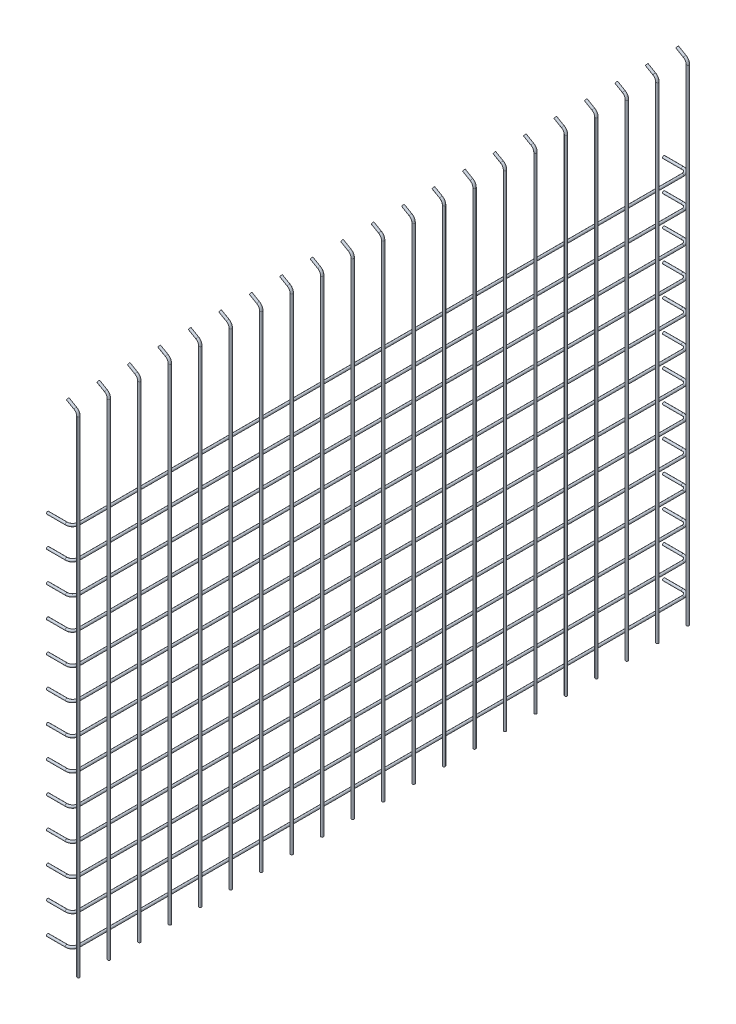
SolidWorks part; units mm, degrees
material "AISI 1020"
ref_plane "Спереди" through (0, 0, 0) normal (0, 0, 1) x (1, 0, 0)
ref_plane "Сверху" through (0, 0, 0) normal (0, 1, 0) x (1, 0, 0)
ref_plane "Справа" through (0, 0, 0) normal (1, 0, 0) x (0, 0, -1)
sketch "Эскиз1" plane through (0, 0, 0) normal (0, 0, 1) x (1, 0, 0)
  line L0 (-2, 0) -> (-2, 796.993)
  line L1 (-7, 805.6532) -> (-19.3205, 812.7665)
  line L2 (-1694.5, 1782.2412) -> (84.6025, 755.0759) construction
  line L3 (-44, 829.3246) -> (0, 803.9212) construction
  arc A0 (-2, 796.993) -> (-7, 805.6532) centre (-12, 796.993) ccw
  point P8 (0, 0)
  point P11 (-2, 802.7665)
  dimension "D4" = 10
  dimension "D1" = 2
  dimension "D2" = 20
  dimension "D3" = 2
ref_plane "Плоскость1" through (0, 0, 0) normal (0, 1, 0) x (1, 0, 0)
sketch "Эскиз2" plane through (0, 0, 0) normal (0, 1, 0) x (1, 0, 0)
  circle A0 centre (-2, 0) radius 2
  point P2 (0, 0)
  dimension "D1" = 4
sweep "По траектории1" add profiles "Эскиз2" path "Эскиз1"
pattern_linear "Линейный массив1" count 11 spacing 50 along (0, 0, -1) of bodies 103
mirror "Зеркальное отражение1" about plane through (0, 0, 0) normal (0, 0, 1) of bodies 113 112 111 110 109 108 106 105 104 107
ref_plane "Плоскость2" through (0, 40, 0) normal (0, 1, 0) x (1, 0, 0)
sketch "Эскиз3" plane through (0, 40, 0) normal (0, 1, 0) x (1, 0, 0)
  line L0 (-47, 505.5) -> (-16, 505.5)
  line L1 (-6, 495.5) -> (-6, -495.5)
  line L2 (-16, -505.5) -> (-47, -505.5)
  line L3 (-1671, -507.5) -> (108.1025, -507.5) construction
  line L4 (-1671, 507.5) -> (108.1025, 507.5) construction
  line L5 (-47, 510.5) -> (-47, 554.5) construction
  circle A0 centre (-2, 0) radius 2 construction
  arc A1 (-6, -495.5) -> (-16, -505.5) centre (-16, -495.5) cw
  arc A2 (-16, 505.5) -> (-6, 495.5) centre (-16, 495.5) cw
  point P10 (0, 0)
  dimension "D1" = 4
  dimension "D4" = 10
  dimension "D2" = 2
  dimension "D3" = 2
sketch "Эскиз4" plane through (-47, 0, 0) normal (-1, 0, 0) x (0, 0, 1)
  circle A0 centre (-505.5, 40) radius 2
  dimension "D1" = 4
sweep "По траектории2" add profiles "Эскиз4" path "Эскиз3"
pattern_linear "Линейный массив2" count 13 spacing 50 along (0, 1, 0) of bodies 124
